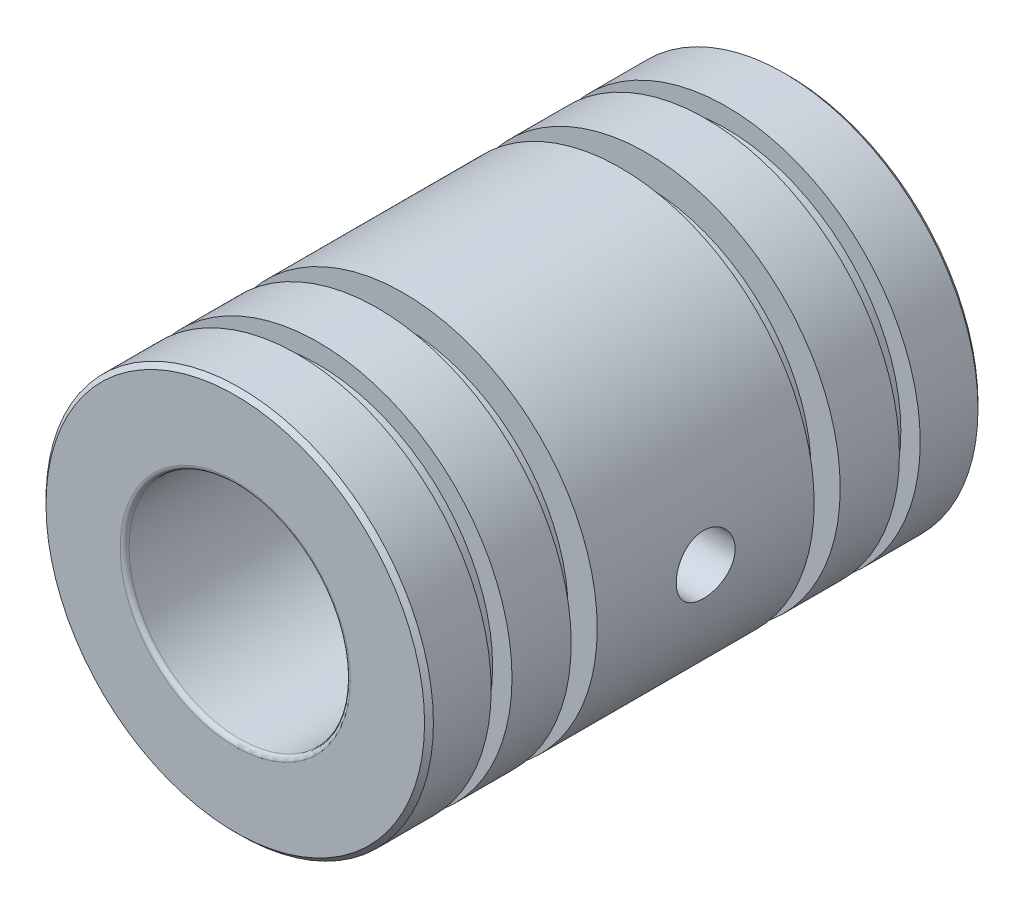
SolidWorks part; units mm, degrees
ref_plane "Front" through (0, 0, 0) normal (0, 0, 1) x (1, 0, 0)
ref_plane "Top" through (0, 0, 0) normal (0, 1, 0) x (1, 0, 0)
ref_plane "Right" through (0, 0, 0) normal (1, 0, 0) x (0, 0, -1)
sketch "Sketch1" plane through (0, 0, 0) normal (1, 0, 0) x (0, 0, -1)
  line L0 (-15.875, 0) -> (15.875, 0)
  line L1 (-15.875, 0) -> (-15.875, -11.1125)
  line L2 (0, 0) -> (0, -11.1125) construction
  line L3 (-15.875, -11.1125) -> (-12.3063, -11.1125)
  line L4 (-12.3063, -11.1125) -> (-12.3063, -10.0012)
  line L5 (-12.3063, -10.0012) -> (-11.1125, -10.0012)
  line L6 (-11.1125, -10.0012) -> (-11.1125, -11.1125)
  line L7 (-15.875, -11.1125) -> (-15.875, 11.1125) construction
  line L8 (11.1125, -11.1125) -> (-11.1125, -11.1125)
  line L9 (15.875, -13.2503) -> (15.875, 13.2503) construction
  line L10 (-12.3063, -11.1125) -> (12.3063, -11.1125) construction
  line L16 (11.1125, -10.0012) -> (11.1125, -11.1125)
  line L17 (12.3063, -10.0012) -> (11.1125, -10.0012)
  line L18 (12.3063, -11.1125) -> (12.3063, -10.0012)
  line L19 (15.875, -11.1125) -> (12.3063, -11.1125)
  line L20 (15.875, 0) -> (15.875, -11.1125)
  line L26 (-15.875, 11.1125) -> (15.875, 11.1125) construction
  point P13 (15.875, 11.1125)
  dimension "D1" = 1.1113
  dimension "D4" = 1.1938
revolve "Bearing" add sketch "Sketch1" angle 360 mid plane about L0
sketch "Sketch2" plane through (0, 0, 0) normal (0, 0, 1) x (1, 0, 0)
  circle A0 centre (0, 0) radius 6.35
  circle A1 centre (0, 0) radius 11.1125 construction
  circle A3 centre (0, 0) radius 11.1125 construction
  dimension "For Shaft Dia" = 12.7
extrude "Bore" cut sketch "Sketch2" against normal through all and the other way through all
sketch "Retaining Hole" plane through (0, 0, 0) normal (1, 0, 0) x (0, 0, -1)
  line L0 (-15.875, 0) -> (15.875, 0) construction
  line L1 (-15.875, 0) -> (-15.875, -11.1125) construction
  circle A0 centre (0, 0) radius 1.6891
  dimension "Supplier H Hole Dia" = 3.3782
  dimension "Supplier I Hole Location" = 15.875
extrude "Retaining Hole " cut sketch "Retaining Hole" along normal through all
fillet "ID Fillet" radius 0.254 2 edges at (6.35, 0, -15.875) (6.35, 0, 15.875)
chamfer "OD Chamfer" distance 0.254 angle 45 2 edges at (11.1125, 0, -15.875) (11.1125, 0, 15.875)
sketch "O-Rings" plane through (0, 0, 0) normal (1, 0, 0) x (0, 0, -1)
  line L0 (6.223, -11.1125) -> (-6.223, -11.1125) construction
  line L1 (-7.7153, -11.1125) -> (-6.223, -11.1125)
  line L2 (-7.7153, -11.1125) -> (-7.7153, -9.4456)
  line L3 (-7.7153, -9.4456) -> (-6.223, -9.4456)
  line L4 (-6.223, -11.1125) -> (-6.223, -9.4456)
  line L5 (6.223, -11.1125) -> (7.7153, -11.1125)
  line L6 (6.223, -11.1125) -> (6.223, -9.4456)
  line L7 (6.223, -9.4456) -> (7.7153, -9.4456)
  line L8 (7.7153, -11.1125) -> (7.7153, -9.4456)
  dimension "D1" = 1.4923
  dimension "D2" = 1.6669
revolve "O-Rings " cut sketch "O-Rings" angle 360 mid plane about L0
equation "\"D1@Sketch1\" = \"OD A@Sketch1\" * .05"
equation "\"D1@O-Rings\" = \"D4@Sketch1\" * 1.25"
equation "\"D2@O-Rings\" = \"D1@Sketch1\" * 1.5"
